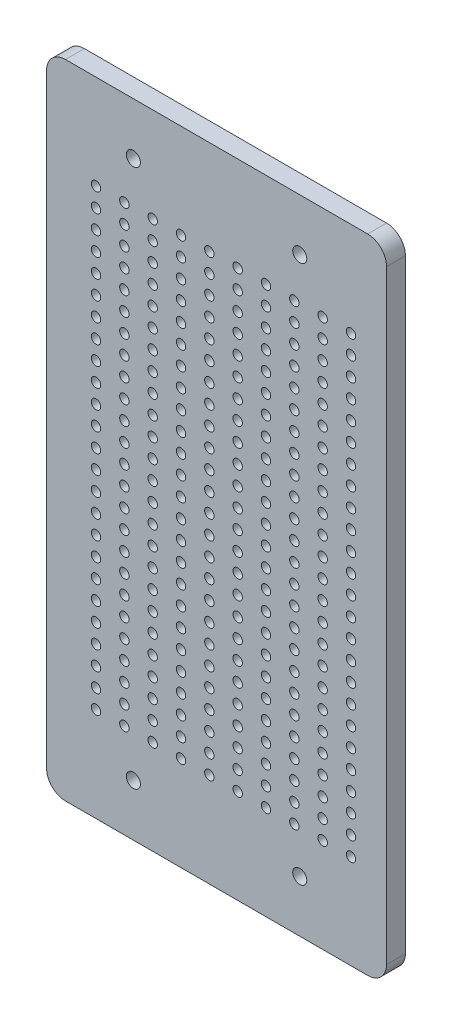
SolidWorks part; units mm, degrees
ref_plane "前视基准面" through (0, 0, 0) normal (0, 0, 1) x (1, 0, 0)
ref_plane "上视基准面" through (0, 0, 0) normal (0, 1, 0) x (1, 0, 0)
ref_plane "右视基准面" through (0, 0, 0) normal (1, 0, 0) x (0, 0, -1)
sketch "草图1" plane through (0, 0, 0) normal (0, 0, 1) x (1, 0, 0)
  line L0 (0, 0) -> (0, -111.1804) construction
  line L1 (-80, 170) -> (80, 170)
  line L2 (-90, 160) -> (-90, -160)
  line L3 (-80, -170) -> (80, -170)
  line L4 (90, 160) -> (90, -160)
  line L5 (-90, 170) -> (90, -170) construction
  line L6 (-90, -170) -> (90, 170) construction
  line L7 (0, 0) -> (-45.1814, 0) construction
  circle A0 centre (-44.05, -142.55) radius 3.725
  circle A1 centre (44.05, -142.55) radius 3.725
  circle A2 centre (44.05, 142.55) radius 3.725
  circle A3 centre (-44.05, 142.55) radius 3.725
  arc A4 (80, 170) -> (90, 160) centre (80, 160) cw
  arc A5 (-80, 170) -> (-90, 160) centre (-80, 160) ccw
  arc A6 (80, -170) -> (90, -160) centre (80, -160) ccw
  arc A7 (-90, -160) -> (-80, -170) centre (-80, -160) ccw
  circle A8 centre (-63.8166, -120) radius 2.5
  circle A9 centre (-48.8166, -120) radius 2.5
  circle A10 centre (-33.8166, -120) radius 2.5
  circle A11 centre (-18.8166, -120) radius 2.5
  circle A12 centre (-3.8166, -120) radius 2.5
  circle A13 centre (11.1834, -120) radius 2.5
  circle A14 centre (26.1834, -120) radius 2.5
  circle A15 centre (41.1834, -120) radius 2.5
  circle A16 centre (56.1834, -120) radius 2.5
  circle A17 centre (71.1834, -120) radius 2.5
  circle A18 centre (-48.8166, -110) radius 2.5
  circle A19 centre (-33.8166, -110) radius 2.5
  circle A20 centre (-18.8166, -110) radius 2.5
  circle A21 centre (-3.8166, -110) radius 2.5
  circle A22 centre (11.1834, -110) radius 2.5
  circle A23 centre (26.1834, -110) radius 2.5
  circle A24 centre (41.1834, -110) radius 2.5
  circle A25 centre (56.1834, -110) radius 2.5
  circle A26 centre (71.1834, -110) radius 2.5
  circle A27 centre (-48.8166, -100) radius 2.5
  circle A28 centre (-33.8166, -100) radius 2.5
  circle A29 centre (-18.8166, -100) radius 2.5
  circle A30 centre (-3.8166, -100) radius 2.5
  circle A31 centre (11.1834, -100) radius 2.5
  circle A32 centre (26.1834, -100) radius 2.5
  circle A33 centre (41.1834, -100) radius 2.5
  circle A34 centre (56.1834, -100) radius 2.5
  circle A35 centre (71.1834, -100) radius 2.5
  circle A36 centre (-48.8166, -90) radius 2.5
  circle A37 centre (-33.8166, -90) radius 2.5
  circle A38 centre (-18.8166, -90) radius 2.5
  circle A39 centre (-3.8166, -90) radius 2.5
  circle A40 centre (11.1834, -90) radius 2.5
  circle A41 centre (26.1834, -90) radius 2.5
  circle A42 centre (41.1834, -90) radius 2.5
  circle A43 centre (56.1834, -90) radius 2.5
  circle A44 centre (71.1834, -90) radius 2.5
  circle A45 centre (-48.8166, -80) radius 2.5
  circle A46 centre (-33.8166, -80) radius 2.5
  circle A47 centre (-18.8166, -80) radius 2.5
  circle A48 centre (-3.8166, -80) radius 2.5
  circle A49 centre (11.1834, -80) radius 2.5
  circle A50 centre (26.1834, -80) radius 2.5
  circle A51 centre (41.1834, -80) radius 2.5
  circle A52 centre (56.1834, -80) radius 2.5
  circle A53 centre (71.1834, -80) radius 2.5
  circle A54 centre (-48.8166, -70) radius 2.5
  circle A55 centre (-33.8166, -70) radius 2.5
  circle A56 centre (-18.8166, -70) radius 2.5
  circle A57 centre (-3.8166, -70) radius 2.5
  circle A58 centre (11.1834, -70) radius 2.5
  circle A59 centre (26.1834, -70) radius 2.5
  circle A60 centre (41.1834, -70) radius 2.5
  circle A61 centre (56.1834, -70) radius 2.5
  circle A62 centre (71.1834, -70) radius 2.5
  circle A63 centre (-48.8166, -60) radius 2.5
  circle A64 centre (-33.8166, -60) radius 2.5
  circle A65 centre (-18.8166, -60) radius 2.5
  circle A66 centre (-3.8166, -60) radius 2.5
  circle A67 centre (11.1834, -60) radius 2.5
  circle A68 centre (26.1834, -60) radius 2.5
  circle A69 centre (41.1834, -60) radius 2.5
  circle A70 centre (56.1834, -60) radius 2.5
  circle A71 centre (71.1834, -60) radius 2.5
  circle A72 centre (-48.8166, -50) radius 2.5
  circle A73 centre (-33.8166, -50) radius 2.5
  circle A74 centre (-18.8166, -50) radius 2.5
  circle A75 centre (-3.8166, -50) radius 2.5
  circle A76 centre (11.1834, -50) radius 2.5
  circle A77 centre (26.1834, -50) radius 2.5
  circle A78 centre (41.1834, -50) radius 2.5
  circle A79 centre (56.1834, -50) radius 2.5
  circle A80 centre (71.1834, -50) radius 2.5
  circle A81 centre (-48.8166, -40) radius 2.5
  circle A82 centre (-33.8166, -40) radius 2.5
  circle A83 centre (-18.8166, -40) radius 2.5
  circle A84 centre (-3.8166, -40) radius 2.5
  circle A85 centre (11.1834, -40) radius 2.5
  circle A86 centre (26.1834, -40) radius 2.5
  circle A87 centre (41.1834, -40) radius 2.5
  circle A88 centre (56.1834, -40) radius 2.5
  circle A89 centre (71.1834, -40) radius 2.5
  circle A90 centre (-48.8166, -30) radius 2.5
  circle A91 centre (-33.8166, -30) radius 2.5
  circle A92 centre (-18.8166, -30) radius 2.5
  circle A93 centre (-3.8166, -30) radius 2.5
  circle A94 centre (11.1834, -30) radius 2.5
  circle A95 centre (26.1834, -30) radius 2.5
  circle A96 centre (41.1834, -30) radius 2.5
  circle A97 centre (56.1834, -30) radius 2.5
  circle A98 centre (71.1834, -30) radius 2.5
  circle A99 centre (-48.8166, -20) radius 2.5
  circle A100 centre (-33.8166, -20) radius 2.5
  circle A101 centre (-18.8166, -20) radius 2.5
  circle A102 centre (-3.8166, -20) radius 2.5
  circle A103 centre (11.1834, -20) radius 2.5
  circle A104 centre (26.1834, -20) radius 2.5
  circle A105 centre (41.1834, -20) radius 2.5
  circle A106 centre (56.1834, -20) radius 2.5
  circle A107 centre (71.1834, -20) radius 2.5
  circle A108 centre (-48.8166, -10) radius 2.5
  circle A109 centre (-33.8166, -10) radius 2.5
  circle A110 centre (-18.8166, -10) radius 2.5
  circle A111 centre (-3.8166, -10) radius 2.5
  circle A112 centre (11.1834, -10) radius 2.5
  circle A113 centre (26.1834, -10) radius 2.5
  circle A114 centre (41.1834, -10) radius 2.5
  circle A115 centre (56.1834, -10) radius 2.5
  circle A116 centre (71.1834, -10) radius 2.5
  circle A117 centre (-48.8166, 0) radius 2.5
  circle A118 centre (-33.8166, 0) radius 2.5
  circle A119 centre (-18.8166, 0) radius 2.5
  circle A120 centre (-3.8166, 0) radius 2.5
  circle A121 centre (11.1834, 0) radius 2.5
  circle A122 centre (26.1834, 0) radius 2.5
  circle A123 centre (41.1834, 0) radius 2.5
  circle A124 centre (56.1834, 0) radius 2.5
  circle A125 centre (71.1834, 0) radius 2.5
  circle A126 centre (-48.8166, 10) radius 2.5
  circle A127 centre (-33.8166, 10) radius 2.5
  circle A128 centre (-18.8166, 10) radius 2.5
  circle A129 centre (-3.8166, 10) radius 2.5
  circle A130 centre (11.1834, 10) radius 2.5
  circle A131 centre (26.1834, 10) radius 2.5
  circle A132 centre (41.1834, 10) radius 2.5
  circle A133 centre (56.1834, 10) radius 2.5
  circle A134 centre (71.1834, 10) radius 2.5
  circle A135 centre (-48.8166, 20) radius 2.5
  circle A136 centre (-33.8166, 20) radius 2.5
  circle A137 centre (-18.8166, 20) radius 2.5
  circle A138 centre (-3.8166, 20) radius 2.5
  circle A139 centre (11.1834, 20) radius 2.5
  circle A140 centre (26.1834, 20) radius 2.5
  circle A141 centre (41.1834, 20) radius 2.5
  circle A142 centre (56.1834, 20) radius 2.5
  circle A143 centre (71.1834, 20) radius 2.5
  circle A144 centre (-48.8166, 30) radius 2.5
  circle A145 centre (-33.8166, 30) radius 2.5
  circle A146 centre (-18.8166, 30) radius 2.5
  circle A147 centre (-3.8166, 30) radius 2.5
  circle A148 centre (11.1834, 30) radius 2.5
  circle A149 centre (26.1834, 30) radius 2.5
  circle A150 centre (41.1834, 30) radius 2.5
  circle A151 centre (56.1834, 30) radius 2.5
  circle A152 centre (71.1834, 30) radius 2.5
  circle A153 centre (-48.8166, 40) radius 2.5
  circle A154 centre (-33.8166, 40) radius 2.5
  circle A155 centre (-18.8166, 40) radius 2.5
  circle A156 centre (-3.8166, 40) radius 2.5
  circle A157 centre (11.1834, 40) radius 2.5
  circle A158 centre (26.1834, 40) radius 2.5
  circle A159 centre (41.1834, 40) radius 2.5
  circle A160 centre (56.1834, 40) radius 2.5
  circle A161 centre (71.1834, 40) radius 2.5
  circle A162 centre (-48.8166, 50) radius 2.5
  circle A163 centre (-33.8166, 50) radius 2.5
  circle A164 centre (-18.8166, 50) radius 2.5
  circle A165 centre (-3.8166, 50) radius 2.5
  circle A166 centre (11.1834, 50) radius 2.5
  circle A167 centre (26.1834, 50) radius 2.5
  circle A168 centre (41.1834, 50) radius 2.5
  circle A169 centre (56.1834, 50) radius 2.5
  circle A170 centre (71.1834, 50) radius 2.5
  circle A171 centre (-48.8166, 60) radius 2.5
  circle A172 centre (-33.8166, 60) radius 2.5
  circle A173 centre (-18.8166, 60) radius 2.5
  circle A174 centre (-3.8166, 60) radius 2.5
  circle A175 centre (11.1834, 60) radius 2.5
  circle A176 centre (26.1834, 60) radius 2.5
  circle A177 centre (41.1834, 60) radius 2.5
  circle A178 centre (56.1834, 60) radius 2.5
  circle A179 centre (71.1834, 60) radius 2.5
  circle A180 centre (-48.8166, 70) radius 2.5
  circle A181 centre (-33.8166, 70) radius 2.5
  circle A182 centre (-18.8166, 70) radius 2.5
  circle A183 centre (-3.8166, 70) radius 2.5
  circle A184 centre (11.1834, 70) radius 2.5
  circle A185 centre (26.1834, 70) radius 2.5
  circle A186 centre (41.1834, 70) radius 2.5
  circle A187 centre (56.1834, 70) radius 2.5
  circle A188 centre (71.1834, 70) radius 2.5
  circle A189 centre (-48.8166, 80) radius 2.5
  circle A190 centre (-33.8166, 80) radius 2.5
  circle A191 centre (-18.8166, 80) radius 2.5
  circle A192 centre (-3.8166, 80) radius 2.5
  circle A193 centre (11.1834, 80) radius 2.5
  circle A194 centre (26.1834, 80) radius 2.5
  circle A195 centre (41.1834, 80) radius 2.5
  circle A196 centre (56.1834, 80) radius 2.5
  circle A197 centre (71.1834, 80) radius 2.5
  circle A198 centre (-48.8166, 90) radius 2.5
  circle A199 centre (-33.8166, 90) radius 2.5
  circle A200 centre (-18.8166, 90) radius 2.5
  circle A201 centre (-3.8166, 90) radius 2.5
  circle A202 centre (11.1834, 90) radius 2.5
  circle A203 centre (26.1834, 90) radius 2.5
  circle A204 centre (41.1834, 90) radius 2.5
  circle A205 centre (56.1834, 90) radius 2.5
  circle A206 centre (71.1834, 90) radius 2.5
  circle A207 centre (-48.8166, 100) radius 2.5
  circle A208 centre (-33.8166, 100) radius 2.5
  circle A209 centre (-18.8166, 100) radius 2.5
  circle A210 centre (-3.8166, 100) radius 2.5
  circle A211 centre (11.1834, 100) radius 2.5
  circle A212 centre (26.1834, 100) radius 2.5
  circle A213 centre (41.1834, 100) radius 2.5
  circle A214 centre (56.1834, 100) radius 2.5
  circle A215 centre (71.1834, 100) radius 2.5
  circle A216 centre (-48.8166, 110) radius 2.5
  circle A217 centre (-33.8166, 110) radius 2.5
  circle A218 centre (-18.8166, 110) radius 2.5
  circle A219 centre (-3.8166, 110) radius 2.5
  circle A220 centre (11.1834, 110) radius 2.5
  circle A221 centre (26.1834, 110) radius 2.5
  circle A222 centre (41.1834, 110) radius 2.5
  circle A223 centre (56.1834, 110) radius 2.5
  circle A224 centre (71.1834, 110) radius 2.5
  circle A225 centre (-48.8166, 120) radius 2.5
  circle A226 centre (-33.8166, 120) radius 2.5
  circle A227 centre (-18.8166, 120) radius 2.5
  circle A228 centre (-3.8166, 120) radius 2.5
  circle A229 centre (11.1834, 120) radius 2.5
  circle A230 centre (26.1834, 120) radius 2.5
  circle A231 centre (41.1834, 120) radius 2.5
  circle A232 centre (56.1834, 120) radius 2.5
  circle A233 centre (71.1834, 120) radius 2.5
  circle A234 centre (-63.8166, -110) radius 2.5
  circle A235 centre (-63.8166, -100) radius 2.5
  circle A236 centre (-63.8166, -90) radius 2.5
  circle A237 centre (-63.8166, -80) radius 2.5
  circle A238 centre (-63.8166, -70) radius 2.5
  circle A239 centre (-63.8166, -60) radius 2.5
  circle A240 centre (-63.8166, -50) radius 2.5
  circle A241 centre (-63.8166, -40) radius 2.5
  circle A242 centre (-63.8166, -30) radius 2.5
  circle A243 centre (-63.8166, -20) radius 2.5
  circle A244 centre (-63.8166, -10) radius 2.5
  circle A245 centre (-63.8166, 0) radius 2.5
  circle A246 centre (-63.8166, 10) radius 2.5
  circle A247 centre (-63.8166, 20) radius 2.5
  circle A248 centre (-63.8166, 30) radius 2.5
  circle A249 centre (-63.8166, 40) radius 2.5
  circle A250 centre (-63.8166, 50) radius 2.5
  circle A251 centre (-63.8166, 60) radius 2.5
  circle A252 centre (-63.8166, 70) radius 2.5
  circle A253 centre (-63.8166, 80) radius 2.5
  circle A254 centre (-63.8166, 90) radius 2.5
  circle A255 centre (-63.8166, 100) radius 2.5
  circle A256 centre (-63.8166, 110) radius 2.5
  circle A257 centre (-63.8166, 120) radius 2.5
  point P0 (0, 0)
  dimension "D3" = 7.45
  dimension "D6" = 10
  dimension "D7" = 5
  dimension "D1" = 180
  dimension "D2" = 340
  dimension "D4" = 285.1
  dimension "D5" = 88.1
  dimension "D10" = 120
  dimension "D8" = 10
  dimension "D9" = 25
extrude "凸台-拉伸1" add sketch "草图1" along normal blind 10
